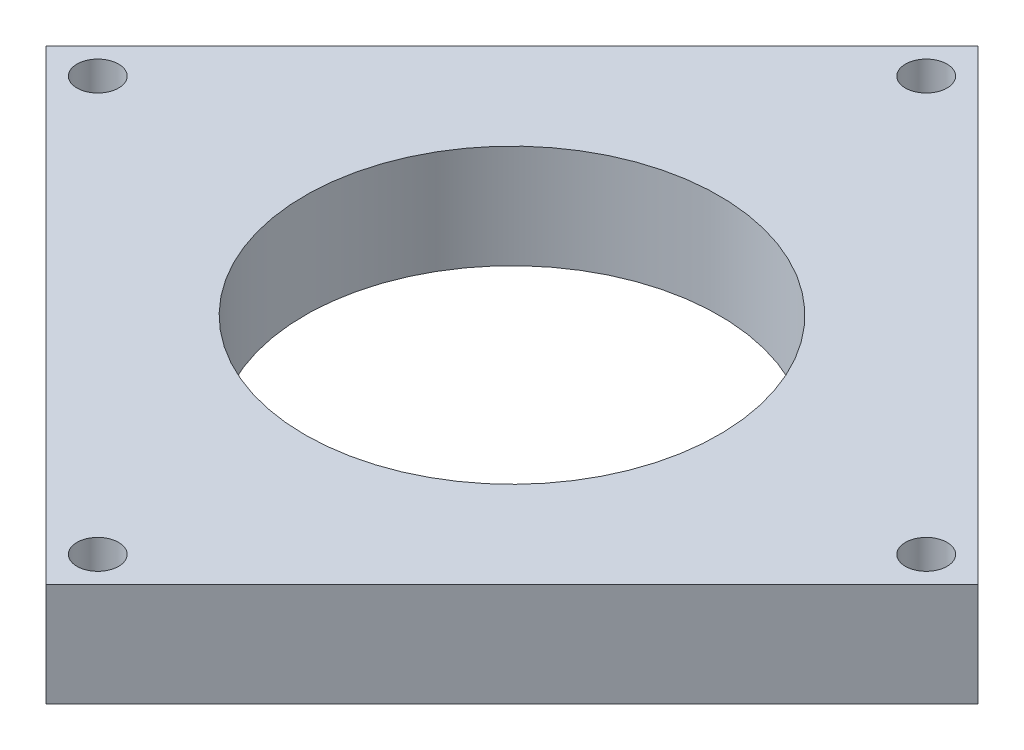
SolidWorks part; units mm, degrees
ref_plane "Front Plane" through (0, 0, 0) normal (0, 0, 1) x (1, 0, 0)
ref_plane "Top Plane" through (0, 0, 0) normal (0, 1, 0) x (1, 0, 0)
ref_plane "Right Plane" through (0, 0, 0) normal (1, 0, 0) x (0, 0, -1)
sketch "Sketch1" plane through (0, 0, 0) normal (0, 1, 0) x (1, 0, 0)
  line L0 (0, -57.15) -> (57.15, 0)
  line L1 (0, -57.15) -> (-57.15, 0)
  line L2 (57.15, 0) -> (0, 57.15)
  line L3 (-57.15, 0) -> (0, 57.15)
  line L4 (0, -57.15) -> (0, 57.15) construction
  line L5 (57.15, 0) -> (-57.15, 0) construction
  dimension "D2" = 114.3
extrude "Boss-Extrude1" add sketch "Sketch1" along normal blind 12.7
sketch "Sketch2" plane through (0, 12.7, 0) normal (0, 1, 0) x (1, 0, 0)
  circle A0 centre (0, 0) radius 25.4
  dimension "D1" = 50.8
extrude "Cut-Extrude1" cut sketch "Sketch2" against normal through all
hole_wizard "#7 (0.201) Diameter Hole1" positions "Sketch4" profile "Sketch3" hole size "#7" standard "Ansi Inch" end condition through all
sketch "Sketch4" plane through (0, 12.7, 0) normal (0, 1, 0) x (-1, 0, 0)
  point P0 (0, -50.8)
  dimension "D1" = 50.8
sketch "Sketch3" plane through (0, 12.7, -50.8) normal (1, 0, 0) x (0, 0, 1)
  line L0 (0, 0) -> (0, 12.7)
  line L1 (0, 12.7) -> (2.5527, 12.7)
  line L2 (2.5527, 12.7) -> (2.5527, 0)
  line L5 (2.5527, 0) -> (0, 0)
  line L11 (0, -6.35) -> (0, 107.95) construction
  dimension "Thru Hole Dia." = 5.1054
  dimension "Thru Hole Depth" = 12.7
pattern_circular "CirPattern1" count 4 over 360 about axis through (0, 0, 0) along (0, 1, 0) of "#7 (0.201) Diameter Hole1"
